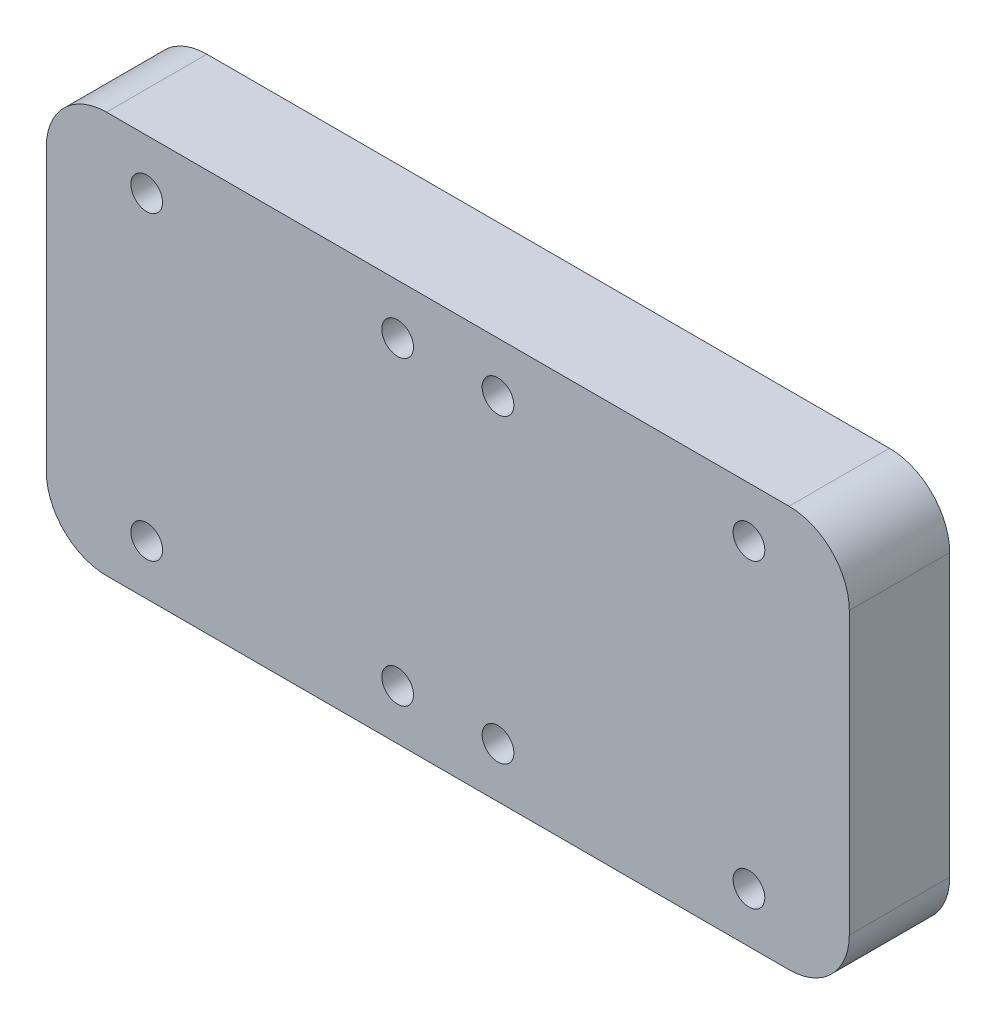
SolidWorks part; units mm, degrees
ref_plane "Plan de face" through (0, 0, 0) normal (0, 0, 1) x (1, 0, 0)
ref_plane "Plan de dessus" through (0, 0, 0) normal (0, 1, 0) x (1, 0, 0)
ref_plane "Plan de droite" through (0, 0, 0) normal (1, 0, 0) x (0, 0, -1)
sketch "Esquisse1" plane through (0, 0, 0) normal (0, 0, 1) x (1, 0, 0)
  line L1 (0, 0) -> (40, 0)
  line L2 (0, 0) -> (0, 20)
  line L3 (0, 20) -> (40, 20)
  line L4 (40, 0) -> (40, 20)
  dimension "D1" = 20
  dimension "D2" = 40
extrude "Boss.-Extru.1" add sketch "Esquisse1" along normal blind 5
fillet "Congé1" radius 3 4 edges at (0, 0, 2.5) (0, 20, 2.5) (40, 0, 2.5) (40, 20, 2.5)
sketch "Esquisse2" plane through (0, 0, 5) normal (0, 0, 1) x (1, 0, 0)
  line L0 (20, 20) -> (20, 0) construction
  line L1 (37, 20) -> (3, 20) construction
  line L2 (3, 0) -> (37, 0) construction
  line L3 (0, 10) -> (40, 10) construction
  line L4 (0, 17) -> (0, 3) construction
  line L5 (40, 3) -> (40, 17) construction
  circle A0 centre (5, 17.5) radius 0.79
  circle A1 centre (5, 2.5) radius 0.79
  circle A2 centre (17.5, 2.5) radius 0.79
  circle A3 centre (17.5, 17.5) radius 0.79
  circle A4 centre (22.5, 17.5) radius 0.79
  circle A5 centre (22.5, 2.5) radius 0.79
  circle A6 centre (35, 2.5) radius 0.79
  circle A7 centre (35, 17.5) radius 0.79
  dimension "D2" = 2.5
  dimension "D3" = 2.5
  dimension "D4" = 12.5
  dimension "D5" = 12.5
  dimension "D6" = 2.5
  dimension "D7" = 1.58
  dimension "D8" = 1.58
  dimension "D9" = 1.58
  dimension "D10" = 1.58
  dimension "D11" = 2.5
  dimension "D12" = 2.5
  dimension "D13" = 2.5
extrude "Enlèv. mat.-Extru.1" cut sketch "Esquisse2" against normal through all
